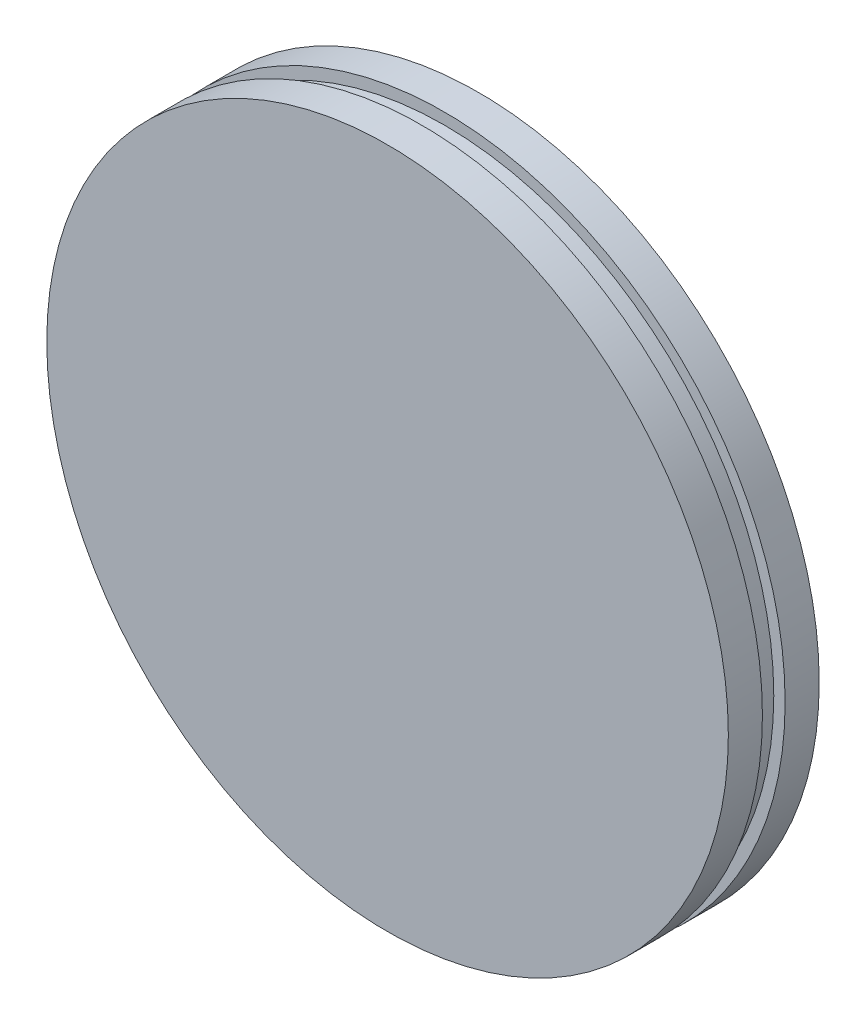
SolidWorks part; units mm, degrees
ref_plane "Plan de face" through (0, 0, 0) normal (0, 0, 1) x (1, 0, 0)
ref_plane "Plan de dessus" through (0, 0, 0) normal (0, 1, 0) x (1, 0, 0)
ref_plane "Plan de droite" through (0, 0, 0) normal (1, 0, 0) x (0, 0, -1)
sketch "Esquisse1" plane through (0, 0, 0) normal (0, 0, 1) x (1, 0, 0)
  line L0 (0, 0) -> (38.8642, 0) construction
  line L1 (0, 0) -> (0, 25.5483) construction
  circle A0 centre (0, 0) radius 11
  circle A1 centre (0, 0) radius 11.5 construction
  circle A3 centre (-16.5, 0) radius 5 construction
  circle A4 centre (0, 0) radius 30
  circle A5 centre (0, 0) radius 22.5 construction
  circle A6 centre (16.5, 0) radius 5 construction
  dimension "D1" = 60
  dimension "D2" = 23
  dimension "D3" = 10
  dimension "D4" = 10
extrude "Boss.-Extru.1" add sketch "Esquisse1" along normal blind 6
sketch "Esquisse2" plane through (0, 0, 6) normal (0, 0, 1) x (1, 0, 0)
  circle A0 centre (0, 0) radius 30
extrude "Boss.-Extru.2" add sketch "Esquisse2" along normal blind 2
ref_plane "Plan1" through (0, 0, 4) normal (0, 0, 1) x (1, 0, 0)
sketch "Esquisse3" plane through (0, 0, 4) normal (0, 0, 1) x (1, 0, 0)
  circle A0 centre (0, 0) radius 30
  circle A1 centre (0, 0) radius 29
  dimension "D1" = 58
  dimension "D2" = 60
extrude "Enlèv. mat.-Extru.1" cut sketch "Esquisse3" against normal blind 1 and the other way blind 1
